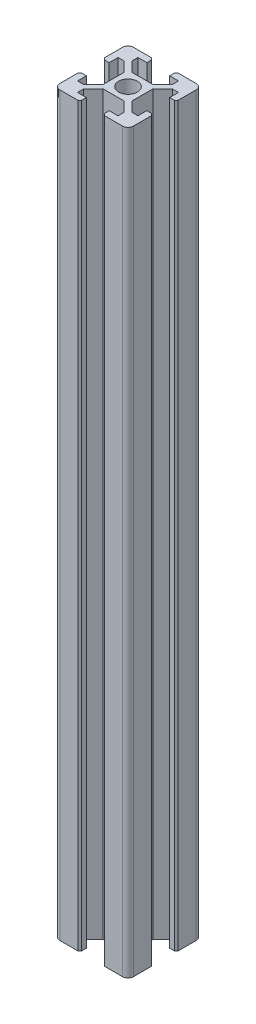
SolidWorks part; units mm, degrees
material "1060 合金"
ref_plane "前视" through (0, 0, 0) normal (0, 0, 1) x (1, 0, 0)
ref_plane "上视" through (0, 0, 0) normal (0, 1, 0) x (1, 0, 0)
ref_plane "右视" through (0, 0, 0) normal (1, 0, 0) x (0, 0, -1)
sketch "草图1" plane through (0, 0, 0) normal (0, 1, 0) x (1, 0, 0)
  line L0 (13.9, 12.8393) -> (13.9, 7.1607)
  line L5 (12.8393, 6.1) -> (7.1607, 6.1)
  line L6 (0, 20) -> (20, 0) construction
  line L7 (20, 20) -> (0, 0) construction
  line L8 (4.5, 18.2) -> (6.9, 18.2)
  line L9 (18.2, 4.5) -> (18.2, 6.9)
  line L10 (4.5, 1.8) -> (6.9, 1.8)
  line L11 (1.8, 4.5) -> (1.8, 6.9)
  line L12 (3.4393, 15.5) -> (6.1, 12.8393)
  line L16 (1.5, 0) -> (6.4, 0)
  line L17 (4.5, 16.5607) -> (7.1607, 13.9)
  line L18 (15.5, 16.5607) -> (12.8393, 13.9)
  line L19 (16.5607, 15.5) -> (13.9, 12.8393)
  line L21 (0, 13.6) -> (0.5, 13.1)
  line L22 (19.4697, 20.5303) -> (-0.5303, 0.5303) construction
  line L23 (20.5303, 19.4697) -> (0.5303, -0.5303) construction
  line L24 (13.9, 7.1607) -> (16.5607, 4.5)
  line L25 (12.8393, 6.1) -> (15.5, 3.4393)
  line L28 (7.1607, 6.1) -> (4.5, 3.4393)
  line L30 (6.1, 7.1607) -> (3.4393, 4.5)
  line L31 (0.5, 6.9) -> (1.8, 6.9)
  line L32 (0.5, 13.1) -> (1.8, 13.1)
  line L33 (6.9, 19.5) -> (6.9, 18.2)
  line L34 (13.1, 19.5) -> (13.1, 18.2)
  line L35 (6.9, 1.8) -> (6.9, 0.5)
  line L36 (6.1, 7.1607) -> (6.1, 12.8393)
  line L37 (13.1, 1.8) -> (13.1, 0.5)
  line L38 (7.1607, 13.9) -> (12.8393, 13.9)
  line L39 (1.8, 13.1) -> (1.8, 15.5)
  line L40 (0, 1.5) -> (0, 6.4)
  line L41 (18.2, 13.1) -> (19.5, 13.1)
  line L42 (1.8, 4.5) -> (3.4393, 4.5)
  line L44 (18.2, 6.9) -> (19.5, 6.9)
  line L46 (13.1, 1.8) -> (15.5, 1.8)
  line L51 (13.1, 18.2) -> (15.5, 18.2)
  line L54 (18.2, 13.1) -> (18.2, 15.5)
  line L56 (4.5, 1.8) -> (4.5, 3.4393)
  line L57 (1.5, 20) -> (6.4, 20)
  line L58 (0, 18.5) -> (0, 13.6)
  line L59 (1.8, 15.5) -> (3.4393, 15.5)
  line L60 (4.5, 18.2) -> (4.5, 16.5607)
  line L61 (18.5, 20) -> (13.6, 20)
  line L62 (20, 18.5) -> (20, 13.6)
  line L63 (18.2, 15.5) -> (16.5607, 15.5)
  line L64 (15.5, 18.2) -> (15.5, 16.5607)
  line L65 (18.5, 0) -> (13.6, 0)
  line L66 (20, 1.5) -> (20, 6.4)
  line L67 (18.2, 4.5) -> (16.5607, 4.5)
  line L68 (15.5, 1.8) -> (15.5, 3.4393)
  line L69 (0, 6.4) -> (0.5, 6.9)
  line L70 (6.4, 0) -> (6.9, 0.5)
  line L72 (13.6, 0) -> (13.1, 0.5)
  line L73 (20, 6.4) -> (19.5, 6.9)
  line L75 (20, 13.6) -> (19.5, 13.1)
  line L76 (13.6, 20) -> (13.1, 19.5)
  line L77 (6.4, 20) -> (6.9, 19.5)
  circle A0 centre (10, 10) radius 2.55
  arc A1 (18.5, 20) -> (20, 18.5) centre (18.5, 18.5) cw
  arc A2 (0, 18.5) -> (1.5, 20) centre (1.5, 18.5) cw
  arc A3 (0, 1.5) -> (1.5, 0) centre (1.5, 1.5) ccw
  arc A4 (20, 1.5) -> (18.5, 0) centre (18.5, 1.5) cw
  point P18 (0, 0)
  dimension "D3" = 5.1
  dimension "D5" = 1.5
  dimension "D6" = 1.5
  dimension "D7" = 1.5
  dimension "D8" = 1.5
  dimension "D1" = 20
  dimension "D2" = 20
extrude "凸台-拉伸2" add sketch "草图1" along normal blind 200 contours L51 L64 L18 L38 L17 L60 L8 L33 L77 L57 A2 L58 L21 L32 L39 L59 L12 L36 L30 L42 L11 L31 L69 L40 A3 L16 L70 L35 L10 L56 L28 L5 L25 L68 L46 L37 L72 L65 A4 L66 L73 L44 L9 L67 L24 L0 L19 L63 L54 L41 L75 L62 A1 L61 L76 L34
sketch "草图4" plane through (0, 0, 0) normal (0, -1, 0) x (1, 0, 0)
  circle A4 centre (10, -10) radius 2.55
  dimension "D1" = 5.1
extrude "切除-拉伸2" cut sketch "草图4" against normal through all
